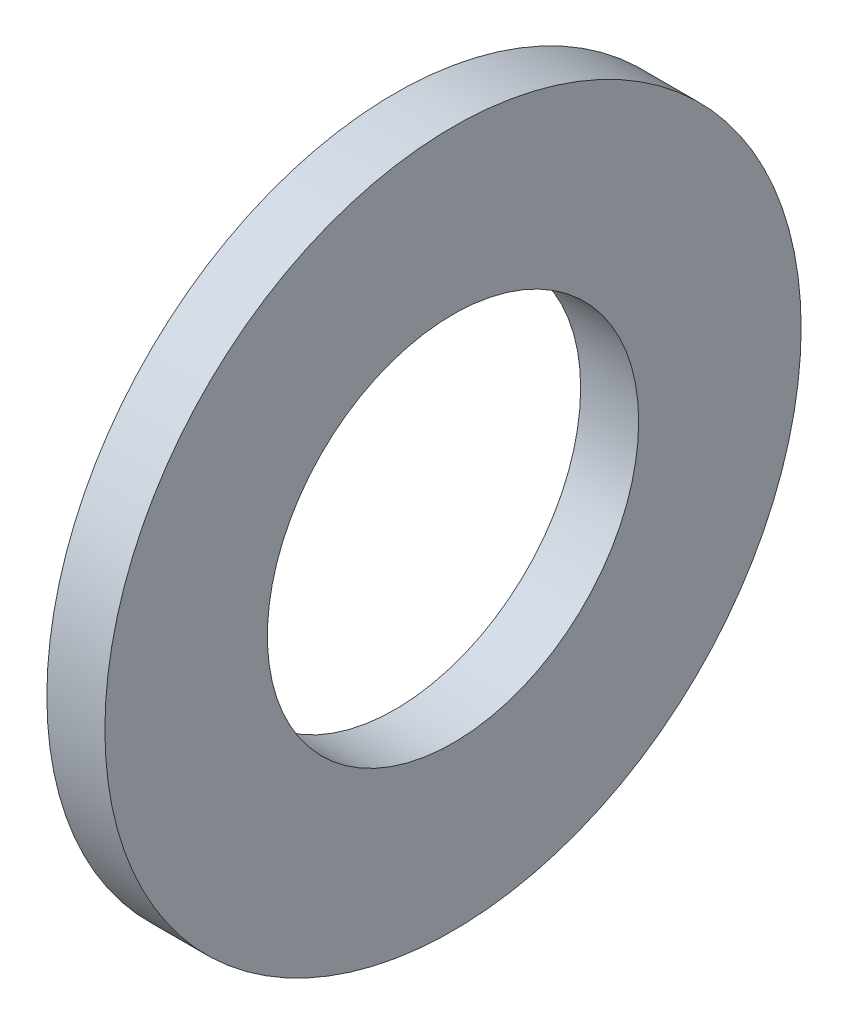
SolidWorks part; units mm, degrees
other "Preload Thrust Washer"
ref_plane "Front Plane" through (0, 0, 0) normal (0, 0, 1) x (1, 0, 0)
ref_plane "Top Plane" through (0, 0, 0) normal (0, 1, 0) x (1, 0, 0)
ref_plane "Right Plane" through (0, 0, 0) normal (1, 0, 0) x (0, 0, -1)
sketch3d "Part ring outside sketch datum points"
  point P0 (19.5, -29, -19.5)
  point P1 (19.5, -19, -19.5)
  point P2 (19.5, -29, -9.5)
ref_plane "Part ring outside sketch plane" through (19.5, 0, 0) normal (1, 0, 0) x (0, 0, -1)
sketch "Part ring outside sketch" plane through (19.5, 0, 0) normal (1, 0, 0) x (0, 0, -1)
  circle A0 centre (19.5, -29) radius 6
extrude "Part ring outside" add sketch "Part ring outside sketch" along normal blind 1 separate body
sketch3d "Part ring bore sketch datum points"
  point P0 (19.4, -29, -19.5)
  point P1 (19.4, -19, -19.5)
  point P2 (19.4, -29, -9.5)
ref_plane "Part ring bore sketch plane" through (19.4, 0, 0) normal (1, 0, 0) x (0, 0, -1)
sketch "Part ring bore sketch" plane through (19.4, 0, 0) normal (1, 0, 0) x (0, 0, -1)
  circle A0 centre (19.5, -29) radius 3.2
extrude "Part ring bore" cut sketch "Part ring bore sketch" along normal blind 1.2
